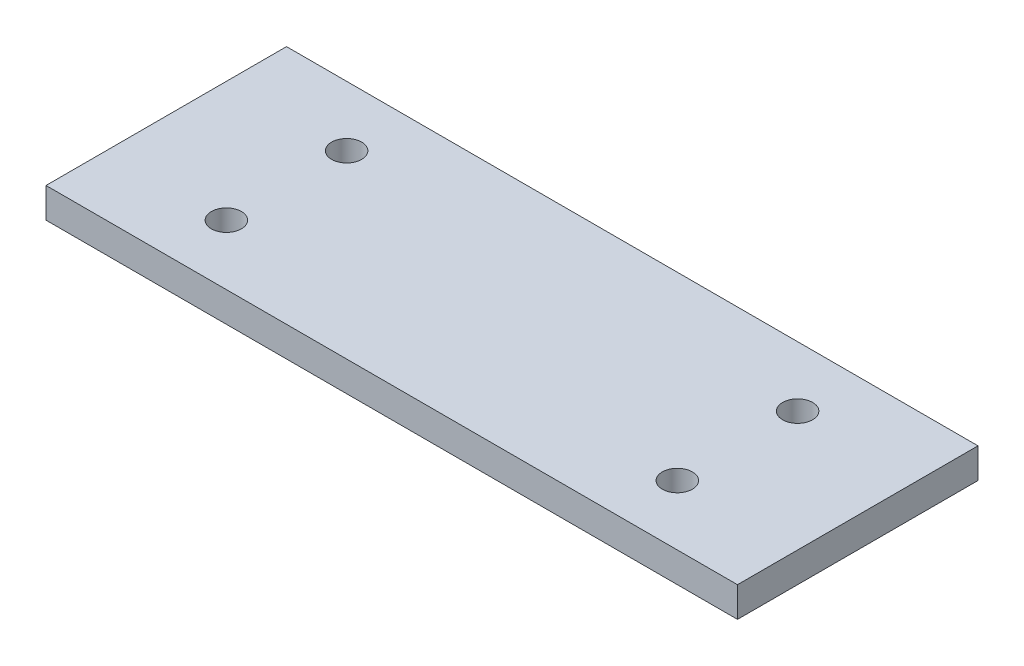
SolidWorks part; units mm, degrees
ref_plane "Front Plane" through (0, 0, 0) normal (0, 0, 1) x (1, 0, 0)
ref_plane "Top Plane" through (0, 0, 0) normal (0, 1, 0) x (1, 0, 0)
ref_plane "Right Plane" through (0, 0, 0) normal (1, 0, 0) x (0, 0, -1)
sketch "Sketch1" plane through (0, 0, 0) normal (0, 1, 0) x (1, 0, 0)
  line L0 (57.5, 40) -> (57.5, 57.2594) construction
  line L1 (0, 0) -> (115, 0)
  line L2 (0, 0) -> (0, 40)
  line L3 (0, 40) -> (115, 40)
  line L4 (115, 0) -> (115, 40)
  line L5 (95, 8.5372) -> (95, 10)
  line L6 (95, 10) -> (95, 30) construction
  circle A0 centre (95, 30) radius 2.5
  circle A1 centre (95, 10) radius 2.5
  circle A2 centre (20, 10) radius 2.5
  circle A3 centre (20, 30) radius 2.5
  point P12 (0, 0)
  point P13 (95, 20)
  point P14 (115, 20)
  dimension "D5" = 5
  dimension "D1" = 115
  dimension "D2" = 40
  dimension "D3" = 20
  dimension "D4" = 20
extrude "Boss-Extrude1" add sketch "Sketch1" along normal blind 5 contours L1 L4 L3 L2 A2 A1 A0 A3
